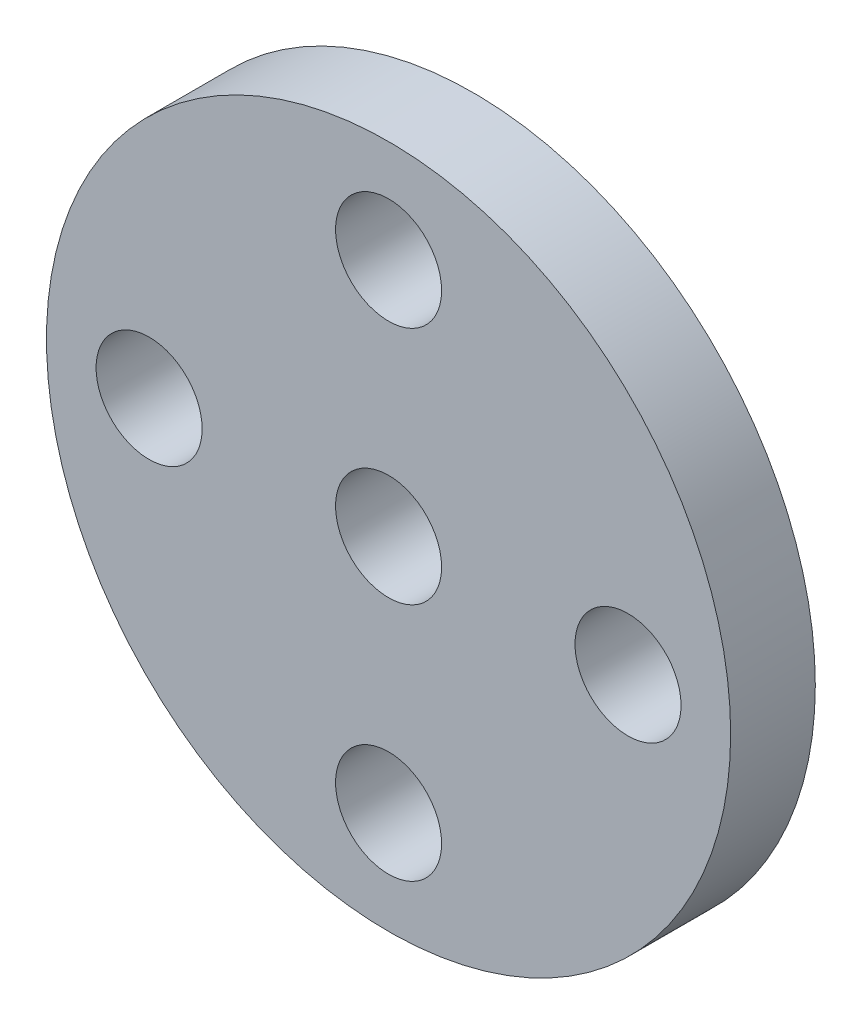
SolidWorks part; units mm, degrees
ref_plane "前视基准面" through (0, 0, 0) normal (0, 0, 1) x (1, 0, 0)
ref_plane "上视基准面" through (0, 0, 0) normal (0, 1, 0) x (1, 0, 0)
ref_plane "右视基准面" through (0, 0, 0) normal (1, 0, 0) x (0, 0, -1)
sketch "草图1" plane through (0, 0, 0) normal (0, 0, 1) x (1, 0, 0)
  circle A0 centre (0, 0) radius 10.1015
  circle A1 centre (0, 0) radius 1.5657
  circle A2 centre (7.0711, 0) radius 1.5657
  circle A3 centre (-7.0711, 0) radius 1.5657
  circle A4 centre (0, 7.0711) radius 1.5657
  circle A5 centre (0, -7.0711) radius 1.5657
  dimension "D1" = 10
  dimension "D2" = 3.1315
extrude "凸台-拉伸1" add sketch "草图1" along normal blind 2.5
sketch "草图2" plane through (0, 0, 0) normal (0, 0, -1) x (-1, 0, 0)
  circle A0 centre (0, 0) radius 4.5
  circle A1 centre (0, 0) radius 3
extrude "凸台-拉伸2" add sketch "草图2" along normal blind 2
